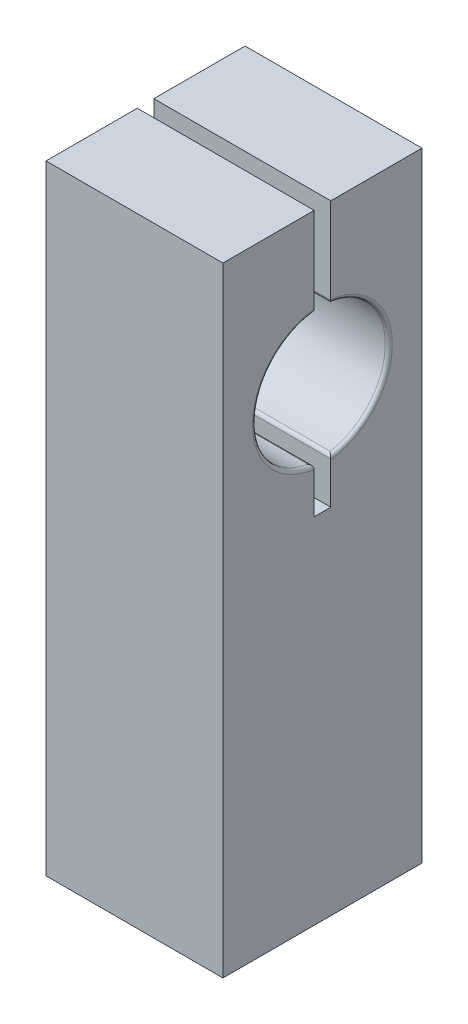
SolidWorks part; units mm, degrees
material "ABS"
ref_plane "Front Plane" through (0, 0, 0) normal (0, 0, 1) x (1, 0, 0)
ref_plane "Top Plane" through (0, 0, 0) normal (0, 1, 0) x (1, 0, 0)
ref_plane "Right Plane" through (0, 0, 0) normal (1, 0, 0) x (0, 0, -1)
sketch "Sketch1" plane through (0, 0, 0) normal (0, 1, 0) x (1, 0, 0)
  line L1 (0, 0) -> (25.4, 0)
  line L2 (0, 0) -> (0, 28.575)
  line L3 (0, 28.575) -> (25.4, 28.575)
  line L4 (25.4, 0) -> (25.4, 28.575)
  dimension "D1" = 28.575
  dimension "D2" = 25.4
extrude "Boss-Extrude1" add sketch "Sketch1" along normal blind 88.9
sketch "Sketch2" plane through (25.4, 0, 0) normal (1, 0, 0) x (0, 0, -1)
  line L0 (13.0969, 50.8) -> (15.4781, 50.8)
  line L1 (15.4781, 50.8) -> (15.4781, 57.2247)
  line L2 (13.0969, 57.2247) -> (13.0969, 50.8)
  line L3 (14.2875, 0) -> (14.2875, 88.9) construction
  line L4 (0, 0) -> (28.575, 0) construction
  line L5 (0, 88.9) -> (28.575, 88.9) construction
  line L6 (13.0969, 76.1253) -> (13.0969, 88.9)
  line L7 (13.0969, 88.9) -> (15.4781, 88.9)
  line L8 (15.4781, 88.9) -> (15.4781, 76.1253)
  arc A0 (15.4781, 57.2247) -> (15.4781, 76.1253) centre (14.2875, 66.675) ccw
  arc A1 (13.0969, 76.1253) -> (13.0969, 57.2247) centre (14.2875, 66.675) ccw
  dimension "D1" = 9.525
  dimension "D2" = 2.3813
  dimension "D3" = 38.1
  dimension "D4" = 66.675
extrude "Cut-Extrude1" cut sketch "Sketch2" against normal up to next
fillet "Fillet1" radius 0.508 8 edges at (12.7, 76.1253, -13.0969) (12.7, 76.1253, -15.4781) (0, 66.675, -23.8125) (0, 66.675, -4.7625) (12.7, 57.2247, -15.4781) (12.7, 57.2247, -13.0969) (25.4, 66.675, -4.7625) (25.4, 66.675, -23.8125)
